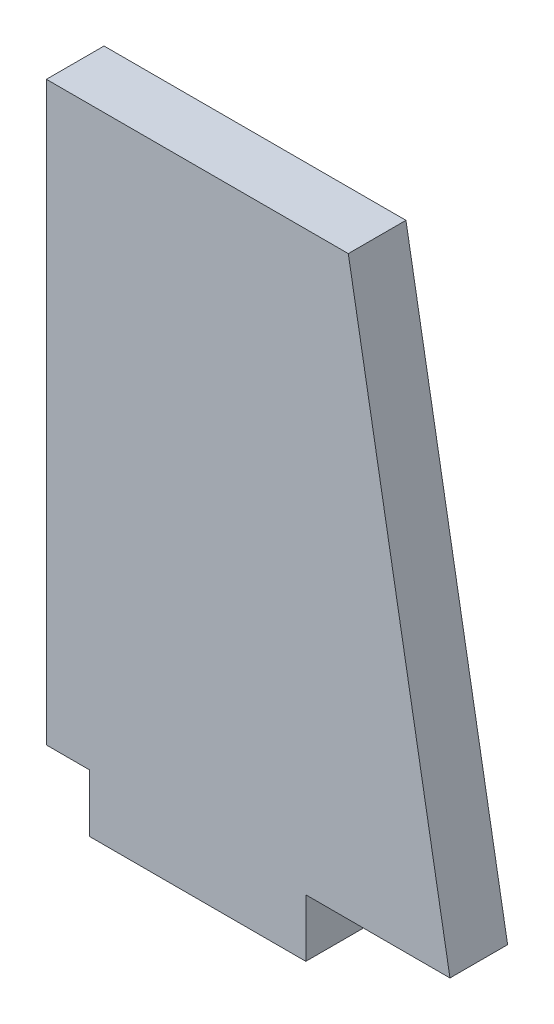
SolidWorks part; units mm, degrees
ref_plane "Front Plane" through (0, 0, 0) normal (0, 0, 1) x (1, 0, 0)
ref_plane "Top Plane" through (0, 0, 0) normal (0, 1, 0) x (1, 0, 0)
ref_plane "Right Plane" through (0, 0, 0) normal (1, 0, 0) x (0, 0, -1)
sketch "Sketch1" plane through (0, 0, 0) normal (0, 0, 1) x (1, 0, 0)
  line L0 (0, 0) -> (-7.0531, 40)
  line L1 (-7.0531, 40) -> (-28, 40)
  line L2 (-28, 40) -> (-28, 0)
  line L3 (-28, 0) -> (-25, 0)
  line L4 (-25, 0) -> (-25, -4)
  line L5 (-25, -4) -> (-10, -4)
  line L6 (-10, -4) -> (-10, 0)
  line L7 (-10, 0) -> (0, 0)
  dimension "D1" = 4
  dimension "D2" = 15
  dimension "D3" = 3
  dimension "D4" = 80
  dimension "D5" = 40
  dimension "D6" = 10
extrude "Boss-Extrude1" add sketch "Sketch1" along normal blind 4
